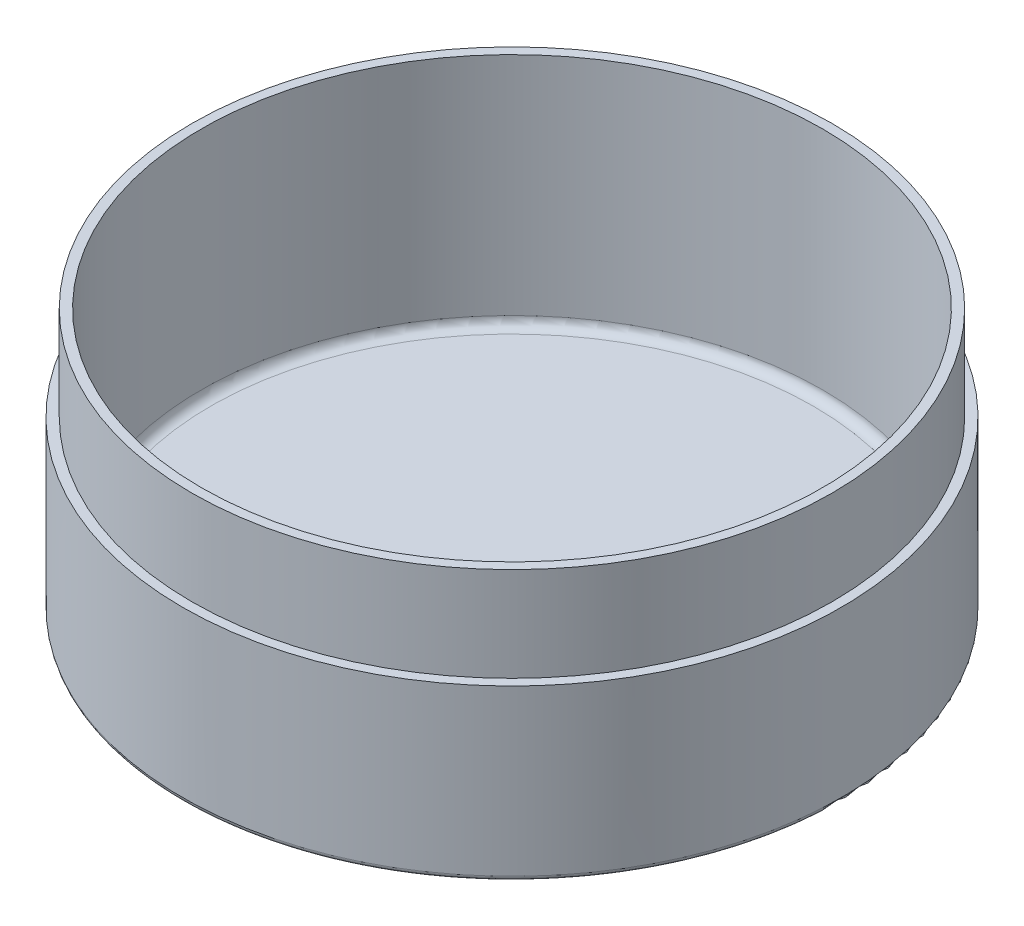
SolidWorks part; units mm, degrees
ref_plane "Спереди" through (0, 0, 0) normal (0, 0, 1) x (1, 0, 0)
ref_plane "Сверху" through (0, 0, 0) normal (0, 1, 0) x (1, 0, 0)
ref_plane "Справа" through (0, 0, 0) normal (1, 0, 0) x (0, 0, -1)
other "Configuration Table"
sketch "Sketch1" plane through (0, 0, 0) normal (0, 1, 0) x (1, 0, 0)
  circle A0 centre (0, 0) radius 35
  circle A1 centre (0, 0) radius 33
  dimension "D1" = 2
  dimension "D2" = 70
extrude "Boss-Extrude1" add sketch "Sketch1" along normal blind 25
sketch "Эскиз1" plane through (0, 0, 0) normal (0, -1, 0) x (1, 0, 0)
  circle A0 centre (0, 0) radius 35
  dimension "D1" = 70
extrude "Бобышка-Вытянуть1" add sketch "Эскиз1" along normal blind 3
sketch "Эскиз3" plane through (0, 25, 0) normal (0, 1, 0) x (1, 0, 0)
  circle A0 centre (0, 0) radius 34
  circle A1 centre (0, 0) radius 35
  dimension "D1" = 1
  dimension "D2" = 68
extrude "Вырез-Вытянуть1" cut sketch "Эскиз3" against normal blind 10
fillet "Скругление1" radius 1 1 edges at (0, 0, 33)
fillet "Скругление2" radius 0.5 1 edges at (0, -3, -35)
equation "\"d\" = 2"
equation "\"v\"=1"
